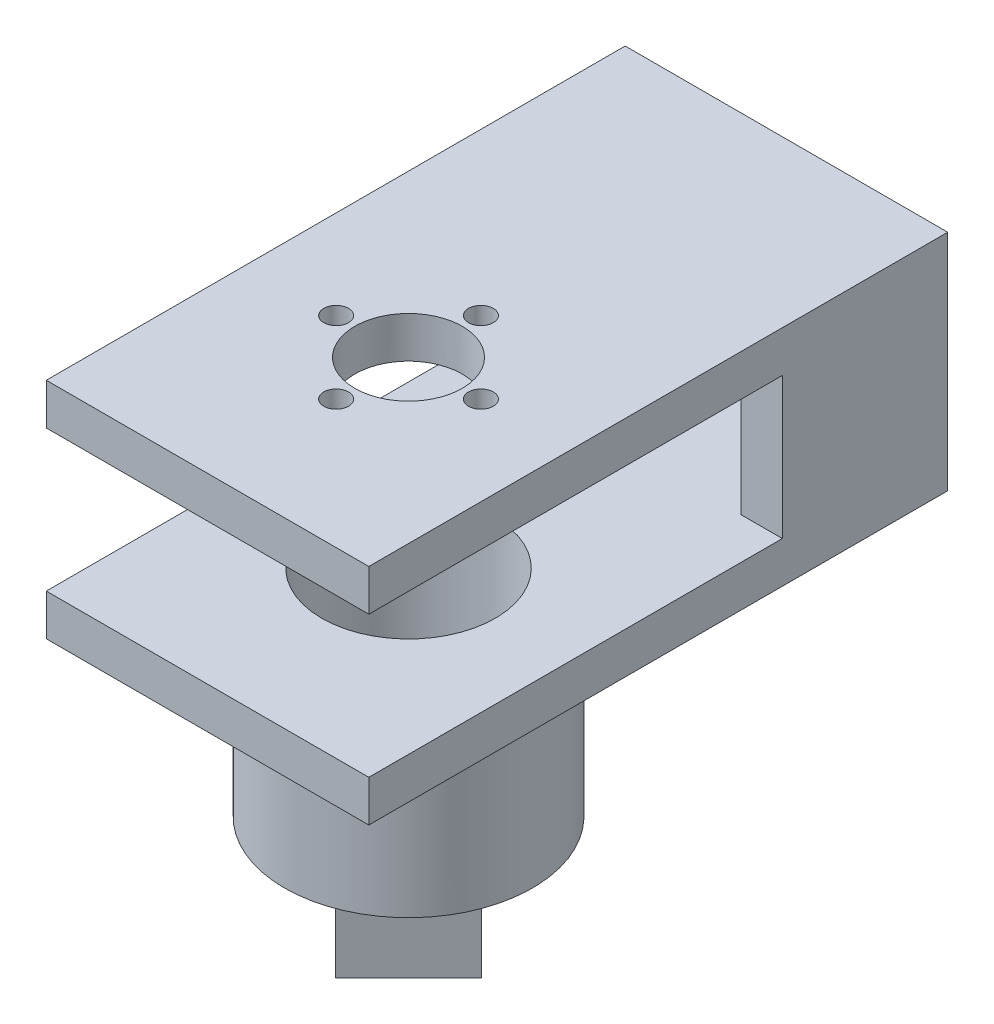
SolidWorks part; units mm, degrees
material "3.0205 (EN-AW 1200)"
ref_plane "前视基准面" through (0, 0, 0) normal (0, 0, 1) x (1, 0, 0)
ref_plane "上视基准面" through (0, 0, 0) normal (0, 1, 0) x (1, 0, 0)
ref_plane "右视基准面" through (0, 0, 0) normal (1, 0, 0) x (0, 0, -1)
other "Configuration Table"
sketch "草图1" plane through (0, 0, 0) normal (0, 0, 1) x (1, 0, 0)
  line L1 (0, 0) -> (58, 0)
  line L2 (0, 0) -> (0, -34.1556)
  line L3 (0, -34.1556) -> (58, -34.1556)
  line L4 (58, 0) -> (58, -34.1556)
  dimension "D1" = 58
extrude "拉伸-薄壁1" add sketch "草图1" along normal blind 40 thin thin type one direction wall 10
sketch "草图2" plane through (0, 0, 40) normal (0, 0, 1) x (1, 0, 0)
  line L0 (-10, -34.1556) -> (68, -34.1556)
  line L4 (-10, 10) -> (-10, -44.1556)
  line L5 (-10, -44.1556) -> (68, -44.1556)
  line L6 (68, -44.1556) -> (68, 10)
  line L7 (68, 10) -> (-10, 10)
  line L8 (-10, -34.1556) -> (-10, -44.1556)
  line L9 (-10, -44.1556) -> (68, -44.1556)
  line L10 (68, -44.1556) -> (68, -34.1556)
  dimension "D1" = 0
extrude "凸台-拉伸1" add sketch "草图2" along normal blind 100
sketch "草图3" plane through (0, 0, 0) normal (0, 0, -1) x (-1, 0, 0)
  line L0 (-58, -29.1556) -> (-58, -34.1556)
  line L1 (-58, -34.1556) -> (-58, 0) construction
  line L2 (-58, -34.1556) -> (-53, -34.1556)
  line L3 (0, -34.1556) -> (-58, -34.1556) construction
  line L4 (-53, -34.1556) -> (-58, -29.1556)
  line L5 (0, -29.1556) -> (0, -34.1556)
  line L6 (0, 0) -> (0, -34.1556) construction
  line L7 (0, -34.1556) -> (-5, -34.1556)
  line L8 (-5, -34.1556) -> (0, -29.1556)
  dimension "D1" = 5
  dimension "D2" = 5
  dimension "D3" = 5
  dimension "D4" = 5
extrude "凸台-拉伸2" add sketch "草图3" against normal blind 5
sketch "草图4" plane through (0, -34.1556, 0) normal (0, 1, 0) x (1, 0, 0)
  line L0 (68, -140) -> (-10, -140) construction
  circle A0 centre (29, -91.3985) radius 21
  point P5 (29, -140)
  dimension "D1" = 42
extrude "切除-拉伸1" cut sketch "草图4" against normal through all
sketch "草图5" plane through (0, 0, 40) normal (0, 0, 1) x (1, 0, 0)
  line L0 (-10, 0) -> (68, 0)
  line L8 (58, -34.1556) -> (68, -34.1556)
  line L9 (68, -34.1556) -> (68, 10)
  line L10 (68, 10) -> (-10, 10)
  line L11 (-10, 10) -> (-10, -34.1556)
  line L12 (-10, -34.1556) -> (0, -34.1556)
  line L13 (0, -34.1556) -> (0, 0)
  line L14 (0, 0) -> (58, 0)
  line L15 (58, 0) -> (58, -34.1556)
  line L17 (68, 0) -> (68, 10)
  line L18 (68, 10) -> (-10, 10)
  line L19 (-10, 10) -> (-10, 0)
  line L22 (0, 0) -> (58, 0)
  line M10 (68, -34.1556) -> (68, 10)
  line M11 (68, 10) -> (-10, 10)
  line M12 (-10, 10) -> (-10, -34.1556)
  line M15 (0, 0) -> (58, 0)
  dimension "D1" = 0
extrude "凸台-拉伸3" add sketch "草图5" along normal up to surface (100 mm away) contours L0 M12 M15 M10 M11 up to face at (29, -39.1556, 140)
sketch "草图6" plane through (0, 10, 0) normal (0, 1, 0) x (1, 0, 0)
  circle A2 centre (29, -91.3985) radius 13
  dimension "D1" = 26
extrude "切除-拉伸2" cut sketch "草图6" against normal up to surface (10 mm away)
sketch "草图8" plane through (0, 10, 0) normal (0, 1, 0) x (1, 0, 0)
  circle A0 centre (29, -91.3985) radius 17.5 construction
  circle A1 centre (29, -73.8985) radius 3
  dimension "D1" = 35
  dimension "D2" = 6
extrude "切除-拉伸3" cut sketch "草图8" against normal blind 35
pattern_circular "阵列(圆周)1" count 4 over 360 about axis through (29, 0, 91.3985) along (0, 1, 0) of "切除-拉伸3"
sketch "草图9" plane through (0, -44.1556, 0) normal (0, -1, 0) x (1, 0, 0)
  circle A0 centre (29, 91.3985) radius 21 construction
  circle A1 centre (29, 91.3985) radius 21
  circle A2 centre (29, 91.3985) radius 30
  dimension "D1" = 60
extrude "凸台-拉伸4" add sketch "草图9" along normal blind 22
cosmetic thread "装饰螺纹线1" parameters "D1"=42, "D2"=54.046
sketch "草图10" plane through (0, -66.1556, 0) normal (0, -1, 0) x (1, 0, 0)
  circle A0 centre (29, 91.3985) radius 30
  circle A1 centre (29, 91.3985) radius 3.5
  dimension "D1" = 7
  dimension "D2" = 60
extrude "凸台-拉伸5" add sketch "草图10" along normal blind 20
sketch "草图12" plane through (0, -86.1556, 0) normal (0, -1, 0) x (1, 0, 0)
  line L0 (18.4449, 68.8332) -> (47.0605, 68.8332) construction
  line L1 (11.3223, 91.3985) -> (29, 109.0762)
  line L2 (11.3223, 91.3985) -> (29, 73.7208)
  line L3 (29, 73.7208) -> (46.6777, 91.3985)
  line L4 (29, 109.0762) -> (46.6777, 91.3985)
  line L5 (11.3223, 91.3985) -> (46.6777, 91.3985) construction
  line L6 (29, 73.7208) -> (29, 109.0762) construction
  point P0 (29, 91.3985)
  dimension "D1" = 25
  dimension "D2" = 45
extrude "凸台-拉伸6" add sketch "草图12" along normal blind 25
